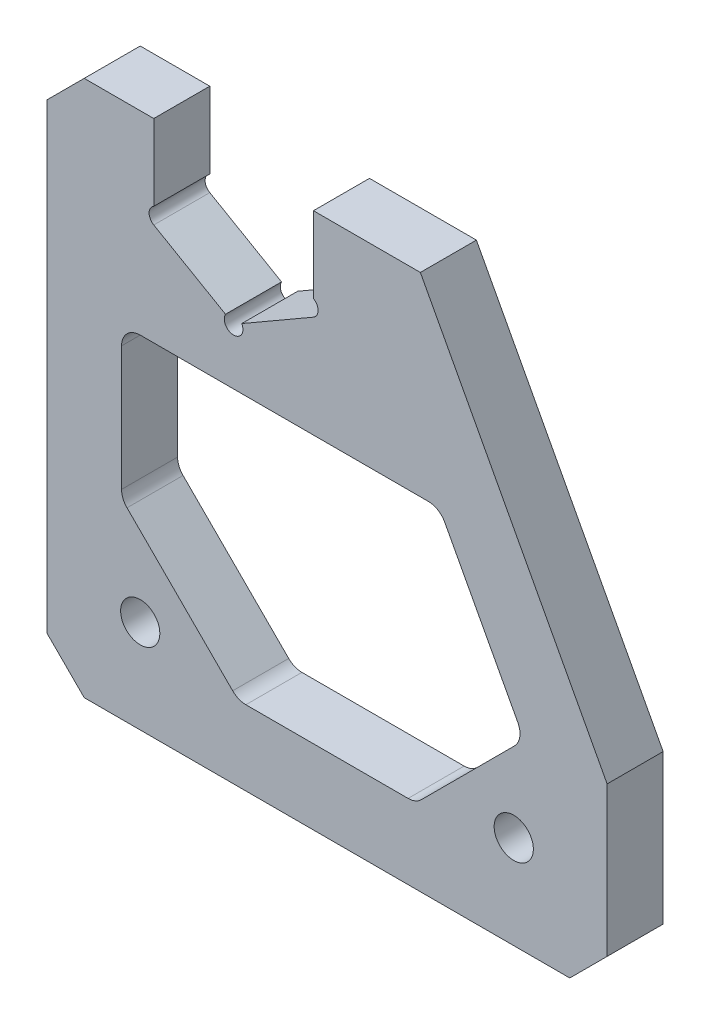
SolidWorks part; units mm, degrees
ref_plane "前视基准面" through (0, 0, 0) normal (0, 0, 1) x (1, 0, 0)
ref_plane "上视基准面" through (0, 0, 0) normal (0, 1, 0) x (1, 0, 0)
ref_plane "右视基准面" through (0, 0, 0) normal (1, 0, 0) x (0, 0, -1)
sketch "草图1" plane through (0, 0, 0) normal (0, 0, 1) x (1, 0, 0)
  line L0 (-20, 4.9363) -> (-20, -52.5)
  line L1 (0, -9.8727) -> (8.55, -4.9363)
  line L2 (8.55, -4.9363) -> (8.55, 4.9363)
  line L3 (8.55, 4.9363) -> (0, 9.8727) construction
  line L4 (0, 9.8727) -> (-8.55, 4.9363) construction
  line L5 (-8.55, 4.9363) -> (-8.55, -4.9363)
  line L6 (-8.55, -4.9363) -> (0, -9.8727)
  line L7 (-20, -52.5) -> (40, -52.5)
  line L8 (-10, -42.5) -> (30, -42.5) construction
  line L11 (40, -32.5) -> (40, -52.5)
  line L13 (20, 4.9363) -> (40, -32.5)
  line L14 (-8.55, 4.9363) -> (-20, 4.9363)
  line L15 (8.55, 4.9363) -> (20, 4.9363)
  circle A0 centre (0, 0) radius 8.55 construction
  circle A1 centre (-10, -42.5) radius 2.1
  circle A2 centre (30, -42.5) radius 2.1
  dimension "D1" = 17.1
  dimension "D4" = 10
  dimension "D6" = 4.2
  dimension "D2" = 20
  dimension "D3" = 52.5
  dimension "D5" = 10
  dimension "D7" = 40
  dimension "D8" = 20
  dimension "D9" = 10
extrude "凸台-拉伸1" add sketch "草图1" along normal mid plane 6
chamfer "倒角1" distance 4 angle 45 3 edges at (40, -52.5, 0) (-20, -52.5, 0) (-20, 4.9363, 0)
sketch "草图2" plane through (0, 0, 3) normal (0, 0, 1) x (1, 0, 0)
  line L0 (0, -9.8727) -> (-8.55, -4.9363) construction
  line L3 (8.55, -4.9363) -> (0, -9.8727) construction
  circle A0 centre (-8.05, -4.0703) radius 1
  circle A1 centre (8.05, -4.0703) radius 1
  circle A2 centre (0, -9.8727) radius 1
  dimension "D1" = 2
extrude "切除-拉伸1" cut sketch "草图2" against normal through all
sketch "草图3" plane through (0, 0, 3) normal (0, 0, 1) x (1, 0, 0)
  line L0 (-12, -15.8727) -> (-12, -32.0147)
  line L1 (-12, -15.8727) -> (22.0469, -15.8727)
  line L2 (22.0469, -15.8727) -> (31.1336, -32.8812)
  line L3 (31.1336, -32.8812) -> (19.5147, -44.5)
  line L4 (19.5147, -44.5) -> (0.4853, -44.5)
  line L5 (0.4853, -44.5) -> (-12, -32.0147)
  line L6 (10, -44.5) -> (10, -52.5) construction
  line L7 (-16, -52.5) -> (36, -52.5) construction
  line L9 (40, -32.5) -> (20, 4.9363) construction
  line L10 (-20, -48.5) -> (-16, -52.5) construction
  line L11 (36, -52.5) -> (40, -48.5) construction
  line L12 (-20, 0.9363) -> (-20, -48.5) construction
  arc A0 (-0.866, -9.3727) -> (0.866, -9.3727) centre (0, -9.8727) ccw construction
  circle A1 centre (-10, -42.5) radius 2.1 construction
  point P21 (-20, -23.7818)
  dimension "D1" = 8
  dimension "D2" = 8
  dimension "D3" = 6
  dimension "D4" = 6
  dimension "D5" = 8
extrude "切除-拉伸2" cut sketch "草图3" against normal through all
fillet "圆角1" radius 2 6 edges at (31.1336, -32.8812, 0) (19.5147, -44.5, 0) (0.4853, -44.5, 0) (-12, -32.0147, 0) (22.0469, -15.8727, 0) (-12, -15.8727, 0)
chamfer "倒角2" distance 2 angle 45 2 edges at (-7.9, -42.5, -3) (32.1, -42.5, -3)
